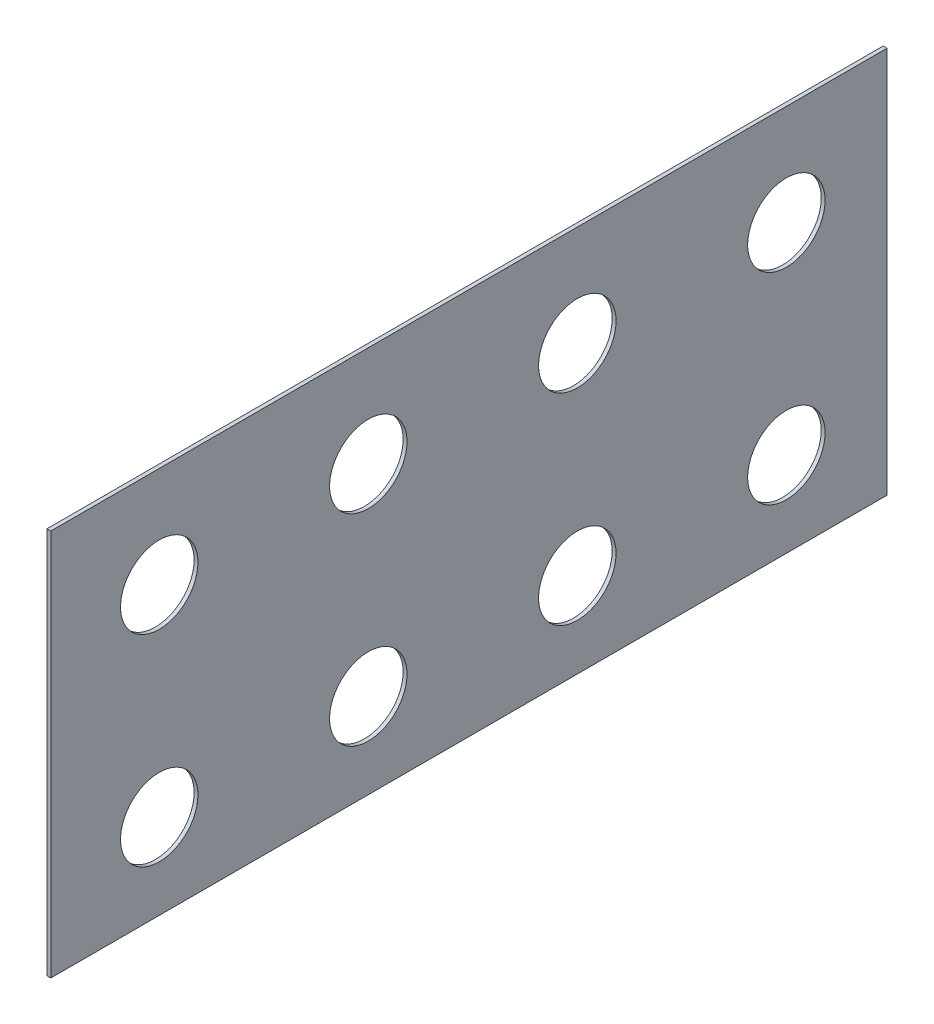
SolidWorks part; units mm, degrees
ref_plane "Alzado" through (0, 0, 0) normal (0, 0, 1) x (1, 0, 0)
ref_plane "Planta" through (0, 0, 0) normal (0, 1, 0) x (1, 0, 0)
ref_plane "Vista lateral" through (0, 0, 0) normal (1, 0, 0) x (0, 0, -1)
sketch "Croquis1" plane through (0, 0, 0) normal (1, 0, 0) x (0, 0, -1)
  line L1 (540, -250) -> (-540, -250)
  line L2 (540, -250) -> (540, 250)
  line L3 (540, 250) -> (-540, 250)
  line L4 (-540, -250) -> (-540, 250)
  line L5 (540, -250) -> (-540, 250) construction
  line L6 (540, 250) -> (-540, -250) construction
  point P0 (0, 0)
  dimension "D1" = 1080
  dimension "D2" = 500
extrude "Extruir1" add sketch "Croquis1" along normal blind 5
sketch "Croquis2" plane through (5, 0, 0) normal (1, 0, 0) x (0, 0, -1)
  line L0 (-520, -250) -> (-520, 250) construction
  line L1 (-540, -250) -> (540, -250) construction
  line L2 (540, 250) -> (-540, 250) construction
  line L4 (-520, 0) -> (520, 0) construction
  line L5 (520, 250) -> (520, -250) construction
  line L6 (0, 0) -> (0, -250) construction
  line L7 (-540, 230) -> (540, 230) construction
  line L8 (-540, 250) -> (-540, -250) construction
  line L9 (540, -250) -> (540, 250) construction
  circle A0 centre (-520, -190) radius 10
  circle A1 centre (520, -190) radius 10
  circle A2 centre (-390, 230) radius 10
  circle A3 centre (390, 230) radius 10
  circle A4 centre (520, 190) radius 10
  circle A5 centre (-520, 190) radius 10
  dimension "D2" = 20
  dimension "D3" = 60
  dimension "D5" = 150
  dimension "D1" = 1040
  dimension "D4" = 20
sketch "Croquis3" plane through (5, 0, 0) normal (1, 0, 0) x (0, 0, -1)
  line L0 (-520, 0) -> (520, 0) construction
  line L1 (0, 0) -> (0, -250) construction
  circle A0 centre (-400, 380) radius 50
  circle A16 centre (-130, 380) radius 50
  circle A17 centre (140, 380) radius 50
  circle A18 centre (410, 380) radius 50
  circle A19 centre (-400, 120) radius 50
  circle A20 centre (-130, 120) radius 50
  circle A21 centre (140, 120) radius 50
  circle A22 centre (410, 120) radius 50
  circle A23 centre (-400, -140) radius 50
  circle A24 centre (-130, -140) radius 50
  circle A25 centre (140, -140) radius 50
  circle A26 centre (410, -140) radius 50
  circle A27 centre (-400, -400) radius 50
  circle A28 centre (-130, -400) radius 50
  circle A29 centre (140, -400) radius 50
  circle A30 centre (410, -400) radius 50
  point P0 (-400, 380)
  dimension "D3" = 100
  dimension "D1" = 380
  dimension "D2" = 400
extrude "Extruir2" cut sketch "Croquis3" against normal through all
